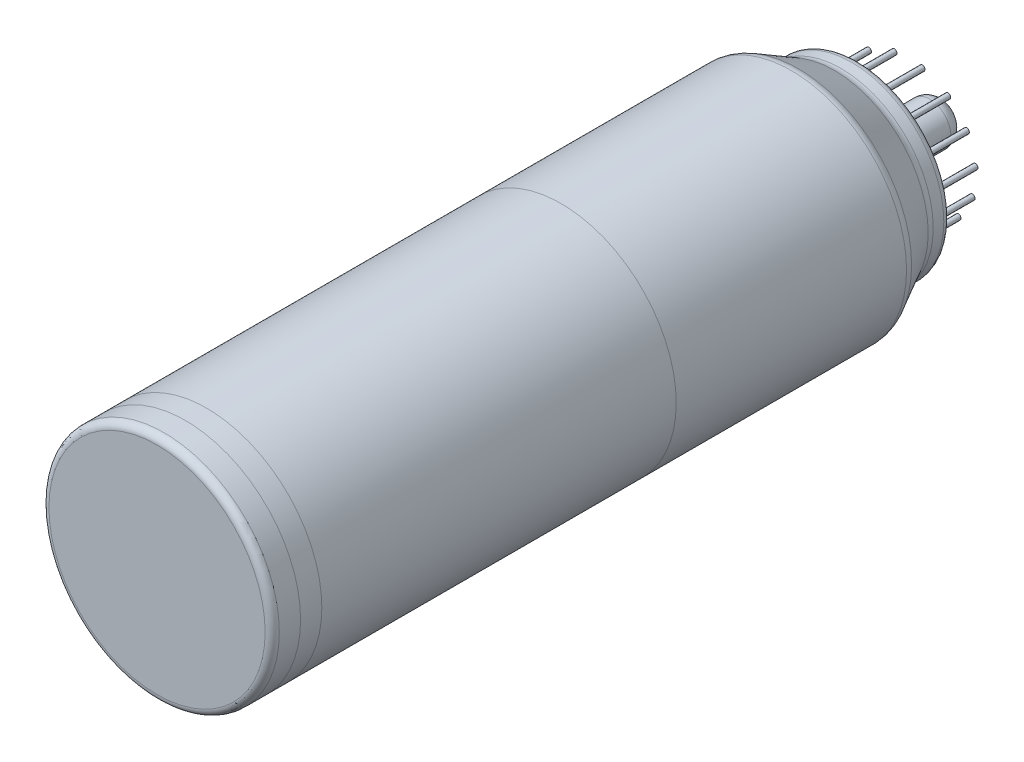
SolidWorks part; units mm, degrees
material "Glass"
ref_plane "Front Plane" through (0, 0, 0) normal (0, 0, 1) x (1, 0, 0)
ref_plane "Top Plane" through (0, 0, 0) normal (0, 1, 0) x (1, 0, 0)
ref_plane "Right Plane" through (0, 0, 0) normal (1, 0, 0) x (0, 0, -1)
sketch "Sketch1" plane through (0, 0, 0) normal (1, 0, 0) x (0, 0, -1)
  line L0 (0, 0) -> (0, 16.25)
  line L1 (0, 16.25) -> (90, 16.25)
  line L2 (90, 16.25) -> (96, 13)
  line L3 (96, 13) -> (99, 13)
  line L4 (99, 13) -> (99, 3)
  line L5 (99, 3) -> (111, 3)
  line L7 (111, 3) -> (111, 0)
  line L8 (111, 0) -> (0, 0)
  line L9 (111, 0) -> (128.9105, 0) construction
  point P4 (111, 3)
  point P12 (111, 2.7042)
  dimension "D1" = 32.5
  dimension "D2" = 99
  dimension "D3" = 3
  dimension "D4" = 26
  dimension "D5" = 6
  dimension "D6" = 6
  dimension "D7" = 111
revolve "Revolve1" add sketch "Sketch1" angle 360 about L9
fillet "Fillet1" radius 1 2 edges at (13, 0, -99) (16.25, 0, 0)
fillet "Fillet2" radius 2 4 edges at (3, 0, -99) (3, 0, -111) (13, 0, -96) (16.25, 0, -90)
sketch "Sketch2" plane through (0, 0, -99) normal (0, 0, -1) x (-1, 0, 0)
  line L0 (3.864, -8.6787) -> (0, 0) construction
  line L1 (0, 0) -> (0, -9.5) construction
  circle A0 centre (0, 0) radius 9.5 construction
  circle A1 centre (3.864, -8.6787) radius 0.375
  dimension "D1" = 19
  dimension "D2" = 0.75
  dimension "D3" = 24
extrude "Boss-Extrude1" add sketch "Sketch2" along normal blind 7
pattern_circular "CirPattern1" count 14 every 24 about axis through (0, 0, 0) along (0, 0, 1) of "Boss-Extrude1"
sketch "Sketch3" plane through (0, 0, 0) normal (0, 1, 0) x (1, 0, 0)
  line L0 (-16.25, 4) -> (16.25, 4)
  line L1 (-16.25, 89.4931) -> (-16.25, 1) construction
  line L2 (16.25, 1) -> (16.25, 89.4931) construction
  line L3 (-16.25, 7) -> (16.25, 7)
  line L4 (16.25, 57) -> (-16.25, 57)
  line L5 (-15.25, 0) -> (15.25, 0) construction
  dimension "D1" = 4
  dimension "D2" = 3
  dimension "D3" = 50
split line "Split Line1"
equation "\"D3@Sketch2\"=360/15"
equation "\"D2@CirPattern1\"=360/15"
